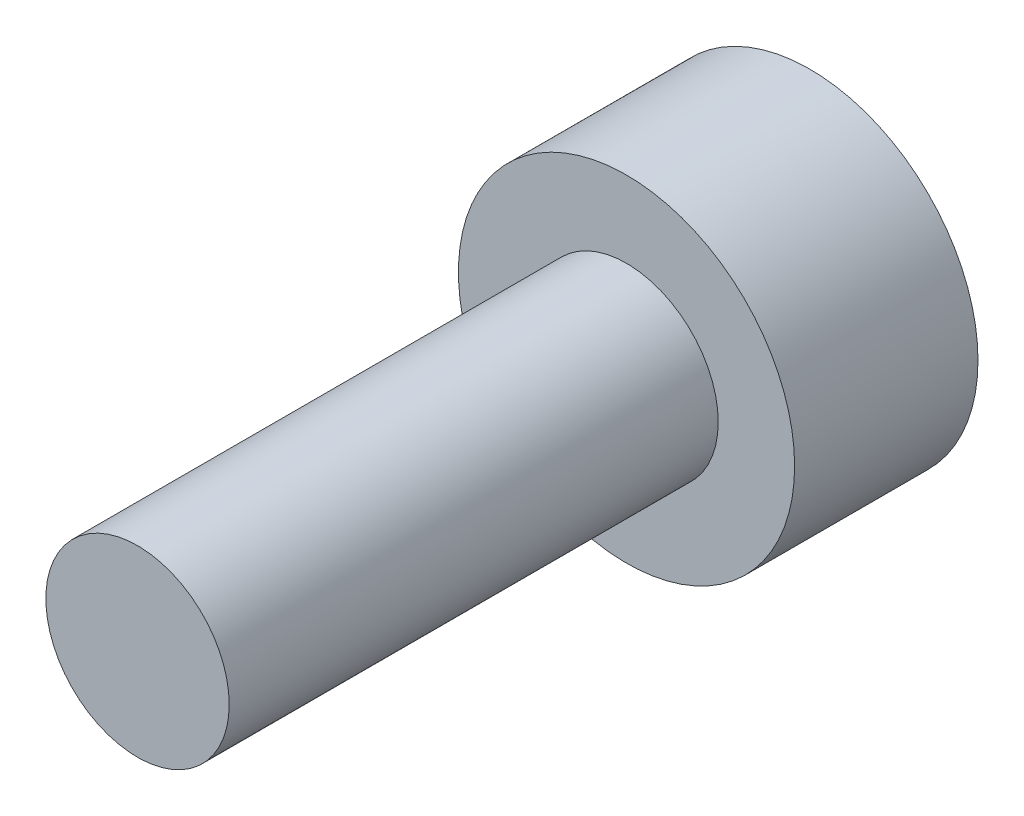
SolidWorks part; units mm, degrees
ref_plane "Plano frontal" through (0, 0, 0) normal (0, 0, 1) x (1, 0, 0)
ref_plane "Plano superior" through (0, 0, 0) normal (0, 1, 0) x (1, 0, 0)
ref_plane "Plano direito" through (0, 0, 0) normal (1, 0, 0) x (0, 0, -1)
sketch "Esboço1" plane through (0, 0, 0) normal (0, 0, 1) x (1, 0, 0)
  circle A0 centre (0, 0) radius 2.75
  dimension "D1" = 5.5
extrude "Ressalto-extrusão1" add sketch "Esboço1" along normal blind 3
sketch "Esboço2" plane through (0, 0, 3) normal (0, 0, 1) x (1, 0, 0)
  circle A0 centre (0, 0) radius 1.5
  dimension "D1" = 3
extrude "Ressalto-extrusão2" add sketch "Esboço2" along normal blind 8
